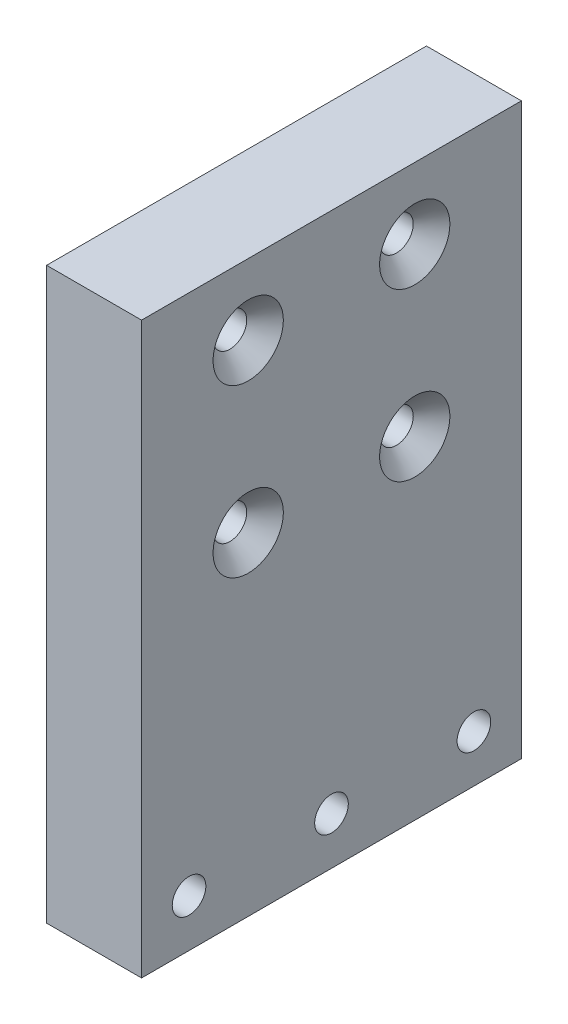
SolidWorks part; units mm, degrees
ref_plane "Front Plane" through (0, 0, 0) normal (0, 0, 1) x (1, 0, 0)
ref_plane "Top Plane" through (0, 0, 0) normal (0, 1, 0) x (1, 0, 0)
ref_plane "Right Plane" through (0, 0, 0) normal (1, 0, 0) x (0, 0, -1)
sketch "Sketch1" plane through (0, 0, 0) normal (1, 0, 0) x (0, 0, -1)
  line L1 (-25.4, -38.1) -> (25.4, -38.1)
  line L2 (-25.4, -38.1) -> (-25.4, 38.1)
  line L3 (-25.4, 38.1) -> (25.4, 38.1)
  line L4 (25.4, -38.1) -> (25.4, 38.1)
  line L5 (-25.4, -38.1) -> (25.4, 38.1) construction
  line L6 (-25.4, 38.1) -> (25.4, -38.1) construction
  point P0 (0, 0)
  dimension "D1" = 50.8
  dimension "D2" = 76.2
extrude "Boss-Extrude1" add sketch "Sketch1" along normal blind 12.7
hole_wizard "CSK for M4 Flat Head Machine Screw1" positions "Sketch3" profile "Sketch2" countersink size "M4" standard "ANSI Metric" end condition through all
sketch "Sketch3" plane through (12.7, 0, 0) normal (1, 0, 0) x (0, 0, -1)
  line L1 (-11.1369, 6.35) -> (11.1369, 6.35) construction
  line L2 (-11.1369, 6.35) -> (-11.1369, 28.6239) construction
  line L3 (-11.1369, 28.6239) -> (11.1369, 28.6239) construction
  line L4 (11.1369, 6.35) -> (11.1369, 28.6239) construction
  line L5 (-11.1369, 6.35) -> (11.1369, 28.6239) construction
  line L6 (-11.1369, 28.6239) -> (11.1369, 6.35) construction
  line L8 (25.4, 38.1) -> (-25.4, 38.1) construction
  point P219 (11.1369, 28.6239)
  point P223 (-11.1369, 28.6239)
  point P225 (-11.1369, 6.35)
  point P227 (11.1369, 6.35)
  dimension "D1" = 31.5
  dimension "D2" = 31.75
sketch "Sketch2" plane through (12.7, 28.6239, -11.1369) normal (0, 1, 0) x (0, 0, -1)
  line L0 (0, 0) -> (0, 12.7)
  line L1 (0, 12.7) -> (2.25, 12.7)
  line L2 (2.25, 12.7) -> (2.25, 2.45)
  line L3 (2.25, 2.45) -> (4.7, 0)
  line L5 (4.7, 0) -> (0, 0)
  line L6 (-2.25, 2.45) -> (-4.7, 0) construction
  line L11 (0, -6.35) -> (0, 107.95) construction
  dimension "Thru Hole Dia." = 4.5
  dimension "Thru Hole Depth" = 12.7
  dimension "Near C'Sink Dia." = 9.4
  dimension "Near C'Sink Angle" = 90
hole_wizard "CBORE for #8 Binding Head Machine Screw1" positions "Sketch5" profile "Sketch4" counterbore size "#8" standard "ANSI Inch" end condition through all
sketch "Sketch5" plane through (0, 0, 0) normal (-1, 0, 0) x (0, 0, 1)
  line L0 (-25.4, -31.75) -> (25.4, -31.75) construction
  line L1 (-25.4, -38.1) -> (-25.4, 38.1) construction
  line L2 (25.4, 38.1) -> (25.4, -38.1) construction
  line L4 (25.4, -38.1) -> (-25.4, -38.1) construction
  line L5 (0, -38.1) -> (0, 0) construction
  point P0 (-19.05, -31.75)
  point P2 (0, -31.75)
  point P4 (19.05, -31.75)
  dimension "D1" = 6.35
  dimension "D2" = 6.35
  dimension "D3" = 6.35
sketch "Sketch4" plane through (0, -31.75, -19.05) normal (0, 1, 0) x (0, 0, 1)
  line L0 (0, 0) -> (0, 12.7)
  line L1 (0, 12.7) -> (2.2479, 12.7)
  line L3 (2.2479, 12.7) -> (2.2479, 2.667)
  line L4 (2.2479, 2.667) -> (4.7625, 2.667)
  line L5 (4.7625, 2.667) -> (4.7625, 0)
  line L7 (4.7625, 0) -> (0, 0)
  line L11 (0, -6.35) -> (0, 107.95) construction
  dimension "Thru Hole Dia." = 4.4958
  dimension "Thru Hole Depth" = 12.7
  dimension "C'Bore Dia." = 9.525
  dimension "C'Bore Depth" = 2.667
